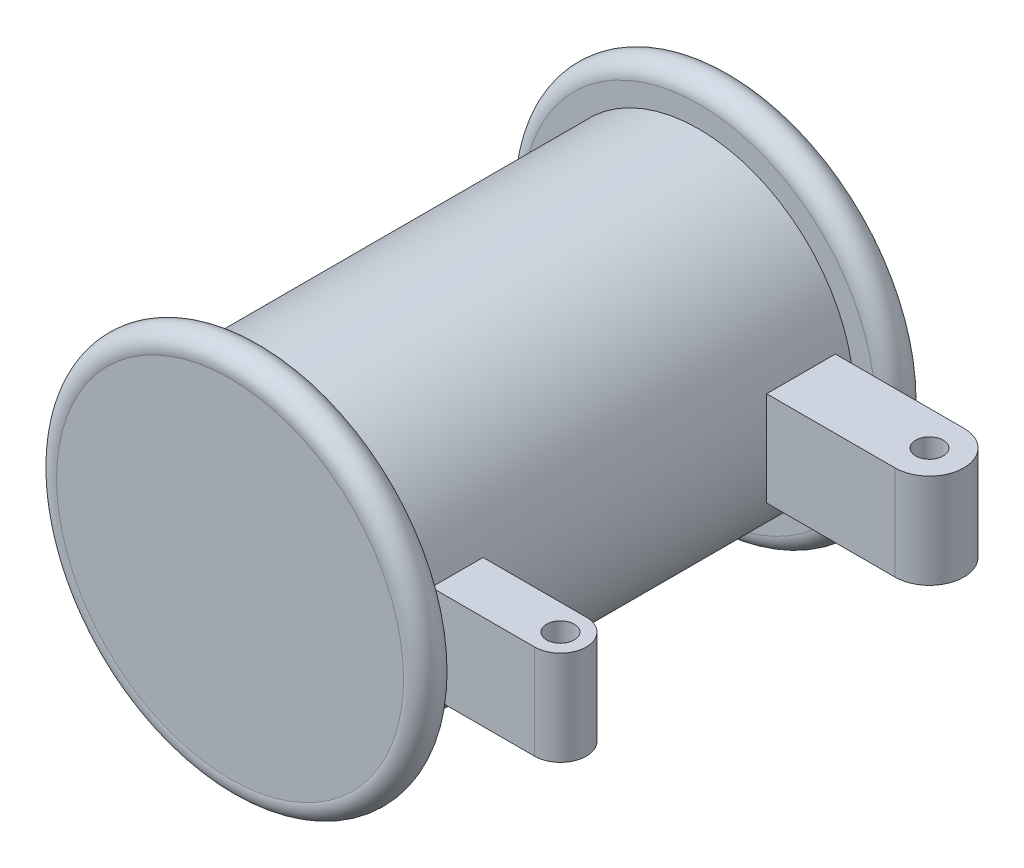
SolidWorks part; units mm, degrees
ref_plane "Front Plane" through (0, 0, 0) normal (0, 0, 1) x (1, 0, 0)
ref_plane "Top Plane" through (0, 0, 0) normal (0, 1, 0) x (1, 0, 0)
ref_plane "Right Plane" through (0, 0, 0) normal (1, 0, 0) x (0, 0, -1)
sketch "Sketch1" plane through (0, 0, 0) normal (0, 1, 0) x (1, 0, 0)
  line L0 (-3.25, 0) -> (-3.25, 1.8852) construction
  line L4 (3.25, 0) -> (3.25, 3.652) construction
  line L6 (-3.25, 0) -> (3.25, 0) construction
  line L7 (4.535, 3.408) -> (4.379, 3.408)
  line L8 (3.25, 3.652) -> (4.535, 3.652)
  line L9 (3.25, 3.652) -> (3.25, 0)
  line L10 (3.25, 0) -> (4.5113, 0)
  line L12 (4.379, 3.408) -> (4.379, 0.2415)
  line L14 (4.379, 0.2415) -> (4.5356, 0.2415)
  arc A0 (4.535, 3.652) -> (4.535, 3.408) centre (4.535, 3.53) cw
  arc A2 (4.5356, 0.2415) -> (4.5113, 0) centre (4.5356, 0.1195) cw
  point P0 (0, 0)
  point P14 (0, 0)
  point P15 (4.657, 3.53)
  point P16 (4.657, 0.1073)
  point P17 (4.5352, 0.2431)
  point P18 (4.379, 0.2431)
  point P19 (4.5352, 0.2431)
  point P20 (4.379, 0.2415)
  dimension "D2" = 0.122
  dimension "D5" = 0.122
  dimension "D1" = 6.5
  dimension "D3" = 1.407
  dimension "D4" = 1.129
  dimension "D6" = 1.407
  dimension "D7" = 3.652
  dimension "D8" = 3.1665
revolve "Revolve3" add sketch "Sketch1" angle 360 about L4
sketch "Sketch3" plane through (0, 0, 0) normal (0, 1, 0) x (1, 0, 0)
  line L0 (4.535, 3.408) -> (4.379, 3.408)
  line L1 (4.535, 3.408) -> (4.379, 3.408)
  line L2 (4.379, 3.408) -> (4.379, 0.2415)
  line L3 (4.379, 3.408) -> (4.379, 0.2415)
  line L4 (4.379, 0.2415) -> (4.5356, 0.2415)
  line L5 (4.379, 0.2415) -> (4.5356, 0.2415)
  line L6 (4.5356, -0.0025) -> (4.5113, -0.0025)
  line L7 (4.5356, -0.0025) -> (4.5113, -0.0025)
  line L8 (4.5113, -0.0025) -> (1.991, 0)
  line L9 (4.5113, -0.0025) -> (1.991, 0)
  line L10 (1.991, 0) -> (1.9644, -0.0025)
  line L11 (1.991, 0) -> (1.9644, -0.0025)
  line L12 (1.9644, 0.2415) -> (2.121, 0.2415)
  line L13 (1.9644, 0.2415) -> (2.121, 0.2415)
  line L14 (2.121, 0.2415) -> (2.121, 3.408)
  line L15 (2.121, 0.2415) -> (2.121, 3.408)
  line L16 (2.121, 3.408) -> (1.965, 3.408)
  line L17 (2.121, 3.408) -> (1.965, 3.408)
  line L18 (1.965, 3.652) -> (4.535, 3.652)
  line L19 (1.965, 3.652) -> (4.535, 3.652)
  line L20 (4.379, 3.272) -> (5.313, 3.272)
  line L21 (5.313, 2.772) -> (4.379, 2.772)
  line L22 (3.25, 4.3274) -> (3.25, 1.9352) construction
  line L23 (4.379, 0.71) -> (5.13, 0.71)
  line L24 (5.13, 0.334) -> (4.379, 0.334)
  line L26 (3.25, 0.9173) -> (3.25, -1.476) construction
  arc A0 (4.5356, -0.0025) -> (4.5356, 0.2415) centre (4.5356, 0.1195) ccw
  arc A1 (4.5356, -0.0025) -> (4.5356, 0.2415) centre (4.5356, 0.1195) ccw
  arc A2 (1.9644, 0.2415) -> (1.9644, -0.0025) centre (1.9644, 0.1195) ccw
  arc A3 (1.9644, 0.2415) -> (1.9644, -0.0025) centre (1.9644, 0.1195) ccw
  arc A4 (1.965, 3.652) -> (1.965, 3.408) centre (1.965, 3.53) ccw
  arc A5 (1.965, 3.652) -> (1.965, 3.408) centre (1.965, 3.53) ccw
  arc A6 (4.535, 3.408) -> (4.535, 3.652) centre (4.535, 3.53) ccw
  arc A7 (4.535, 3.408) -> (4.535, 3.652) centre (4.535, 3.53) ccw
  arc A8 (5.313, 3.272) -> (5.313, 2.772) centre (5.313, 3.022) cw
  circle A9 centre (5.313, 3.022) radius 0.1
  arc A10 (5.13, 0.71) -> (5.13, 0.334) centre (5.13, 0.522) cw
  circle A11 centre (5.13, 0.522) radius 0.1
  point P34 (0, 0)
  dimension "D2" = 0.25
  dimension "D3" = 0.2
  dimension "D6" = 0.188
  dimension "D7" = 0.2
  dimension "D1" = 0.63
  dimension "D4" = 2.063
  dimension "D5" = 2.5
  dimension "D8" = 1.88
extrude "Boss-Extrude2" add sketch "Sketch3" along normal mid plane 0.688 separate body contours A10 L23 L3 L24 A11 | A8 L20 L3 L21 A9
sketch "Sketch4" plane through (0, 0, 0) normal (0, 1, 0) x (1, 0, 0)
  line L1 (2.121, 3.408) -> (2.121, 0.2415) construction
  line L2 (4.379, 0.2415) -> (4.379, 3.408) construction
  line L3 (1.9644, -0.0025) -> (4.5356, -0.0025) construction
  line L4 (4.535, 3.652) -> (1.965, 3.652) construction
  line L5 (2.121, 3.408) -> (2.121, 0.2415)
  line L6 (4.379, 0.2415) -> (4.379, 3.408)
  line L7 (1.9644, -0.0025) -> (4.5356, -0.0025)
  line L8 (4.535, 3.652) -> (1.965, 3.652)
  line L9 (2.121, 1.8248) -> (4.379, 1.8248) construction
  circle A0 centre (3.25, 1.8248) radius 0.315
  circle A1 centre (3.25, 1.8248) radius 0.165
  dimension "D1" = 0.63
  dimension "D2" = 0.33
